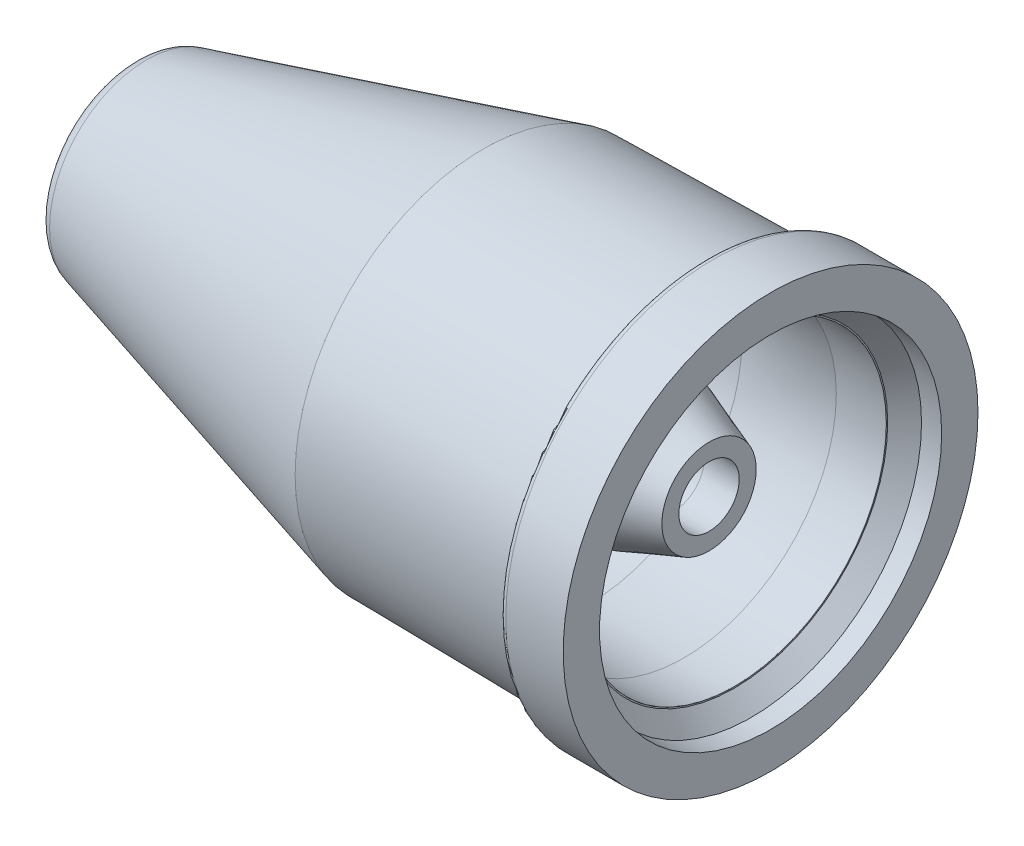
SolidWorks part; units mm, degrees
material "PBT Propósitos gerais"
ref_plane "Frontal" through (0, 0, 0) normal (0, 0, 1) x (1, 0, 0)
ref_plane "Superior" through (0, 0, 0) normal (0, 1, 0) x (1, 0, 0)
ref_plane "Lateral" through (0, 0, 0) normal (1, 0, 0) x (0, 0, -1)
sketch "Sketch1" plane through (0, 0, 0) normal (0, 0, 1) x (1, 0, 0)
  line L0 (3, 0) -> (-11, 0) construction
  line L1 (0, 2.6807) -> (0, 3.25)
  line L2 (0, 3.25) -> (-1, 3.25)
  line L3 (-1, 3.25) -> (-1, 3)
  line L4 (-1, 3) -> (-4.5, 2.951)
  line L5 (-4.5, 2.951) -> (-10, 1.46)
  line L6 (-10, 1.46) -> (-10, 1.1823) construction
  line L7 (-9.57, 0.9) -> (-5.9512, 0.8621) construction
  line L8 (-5.8522, 0.7621) -> (-5.8522, 0.4926)
  line L9 (-5.8522, 0.4926) -> (-1.5277, 0.4926)
  line L10 (-7.53, 1.475) -> (-5.28, 1.475)
  line L11 (-5.28, 1.1084) -> (-1.6842, 1.069)
  line L12 (-5.28, 1.1084) -> (-5.28, 1.25)
  line L13 (-5.28, 1.25) -> (-8.3321, 1.25) construction
  line L14 (-0.3, 2.665) -> (-0.565, 2.4)
  line L15 (-10, 1.1823) -> (-9.8522, 1.1823) construction
  line L16 (-4.81, 2.3268) -> (-0.565, 2.38)
  line L17 (-6.0737, 1.9763) -> (-8.3321, 1.35) construction
  line L18 (-8.3321, 1.35) -> (-8.3321, 1.25) construction
  line L19 (-9.8522, 1.1823) -> (-9.57, 0.9) construction
  line L20 (-4.81, 2.3268) -> (-5.502, 2.1349)
  line L21 (-0.565, 2.38) -> (-0.565, 2.4)
  line L22 (-10, 1.46) -> (-10, 1.182)
  line L23 (-0.3, 2.665) -> (0, 2.6807)
  line L24 (-0.9603, 0.875) -> (-1.6842, 1.069)
  line L25 (-10, 1.182) -> (-9.9422, 1.182)
  line L26 (-9.9422, 1.182) -> (-9.6267, 1.1123)
  line L27 (-9.5482, 1.0147) -> (-9.5482, 0.9111)
  line L28 (-9.5482, 0.9111) -> (-5.9512, 0.8621)
  line L29 (-1.5277, 0.4926) -> (-0.9603, 0.4728)
  line L30 (-0.9603, 0.4728) -> (-0.9603, 0.875)
  line L31 (-5.28, 1.475) -> (-5.28, 1.25)
  line L32 (-7.53, 1.475) -> (-7.53, 1.5724)
  line L33 (-7.53, 1.5724) -> (-6.0737, 1.9763)
  arc A0 (-6.0737, 1.9763) -> (-5.502, 2.1349) centre (-5.8921, 2.4314) ccw
  arc A2 (-9.6267, 1.1123) -> (-9.5482, 1.0147) centre (-9.6482, 1.0147) cw
  arc A3 (-5.8522, 0.7621) -> (-5.9512, 0.8621) centre (-5.9522, 0.7621) ccw
  point P34 (-9.5482, 1.095)
  dimension "D18" = 15.5
  dimension "D27" = 10
  dimension "D31" = 3.8828
  dimension "D7" = 0.601
  dimension "D10" = 0.1
  dimension "D6" = 2.9199
  dimension "D39" = 0.1
  dimension "D37" = 0.49
  dimension "D43" = 0.3
  dimension "D44" = 2.25
  dimension "D46" = 4.8
  dimension "D47" = 5.33
  dimension "D23" = 4.6535
  dimension "D38" = 2.44
  dimension "D48" = 1.8222
  dimension "D52" = 0.1
  dimension "D1" = 6.5
  dimension "D2" = 5.902
  dimension "D3" = 4.5
  dimension "D4" = 1
  dimension "D5" = 3
  dimension "D9" = 4.1478
  dimension "D11" = 0.9852
  dimension "D12" = 1.25
  dimension "D13" = 0.628
  dimension "D14" = 6
  dimension "D15" = 5.28
  dimension "D16" = 4.81
  dimension "D17" = 2.1379
  dimension "D19" = 2.3645
  dimension "D20" = 3.5958
  dimension "D21" = 45
  dimension "D22" = 4.76
  dimension "D24" = 2.7
  dimension "D25" = 2.2167
  dimension "D26" = 3.0521
  dimension "D28" = 0.9603
  dimension "D29" = 45
  dimension "D30" = 8.3321
  dimension "D32" = 1.8
  dimension "D33" = 1.7241
  dimension "D34" = 2.95
  dimension "D35" = 15.168
  dimension "D36" = 5.3614
  dimension "D40" = 0.565
  dimension "D41" = 15
  dimension "D45" = 0.1478
  dimension "D49" = 0.394
  dimension "D50" = 4.09
  dimension "D51" = 2.19
  dimension "D53" = 2.364
  dimension "D54" = 0.9456
  dimension "D56" = 2
revolve "Base-Revolve" add sketch "Sketch1" angle 360 about L0
fillet "Fillet1" radius 0.3 1 edges at (-10, 0, -1.46)
fillet "Fillet2" radius 0.1 1 edges at (-1, 0, -3.25)
scale "Molde (1,5%)" scale about origin uniform scaling yes scale factor 1.015
sketch "Esboço1" plane through (0, 0, 0) normal (0, 0, 1) x (1, 0, 0)
  line L18 (9.9208, -2) -> (9.9208, -0.6)
  line L19 (2.2208, -2) -> (9.9208, -2)
  line L20 (2.2208, -2.1) -> (2.2208, -2)
  line L21 (-0.5792, -2.1) -> (2.2208, -2.1)
  line L22 (-0.5792, -2.425) -> (-0.5792, -2.1)
  line L23 (-1.3798, -2.425) -> (-0.5792, -2.425)
  line L24 (-4.8892, -2.425) -> (-2.8798, -2.425)
  line L25 (-4.9853, -2.3974) -> (-4.8892, -2.425)
  line L26 (-5.7792, -2.1698) -> (-5.6582, -2.2045)
  line L27 (-5.7792, -1.5) -> (-5.7792, -2.1698)
  line L28 (-5.3592, -1.5) -> (-5.7792, -1.5)
  line L29 (-5.3592, -1.125) -> (-5.3592, -1.5)
  line L30 (-1.8996, -1.085) -> (-5.3592, -1.125)
  line L31 (-0.9792, -0.75) -> (-1.8996, -1.085)
  line L32 (-0.9792, -0.48) -> (-0.9792, -0.75)
  line L33 (1.3117, -0.4) -> (-0.9792, -0.48)
  line L34 (1.4272, -0.6) -> (1.3117, -0.4)
  line L35 (9.9208, -0.6) -> (1.4272, -0.6)
  line L40 (-0.5792, -2.425) -> (-0.5735, -0.48)
  line L41 (-1.3798, -2.425) -> (-0.5792, -2.425)
  line L42 (-4.8892, -2.425) -> (-2.8798, -2.425)
  line L43 (-4.9853, -2.3974) -> (-4.8892, -2.425)
  line L44 (-5.7792, -2.1698) -> (-5.6582, -2.2045)
  line L45 (-5.7792, -1.5) -> (-5.7792, -2.1698)
  line L46 (-5.3592, -1.5) -> (-5.7792, -1.5)
  line L47 (-5.3592, -1.125) -> (-5.3592, -1.5)
  line L48 (-1.8996, -1.085) -> (-5.3592, -1.125)
  line L49 (-0.9792, -0.75) -> (-1.8996, -1.085)
  line L50 (-0.9792, -0.48) -> (-0.9792, -0.75)
  line L54 (0, 0) -> (-10.1813, 0) construction
  line L55 (0, -3.2988) -> (0, 3.2988) construction
  line L56 (-0.9792, -0.48) -> (-0.5735, -0.48)
  line L57 (-0.5735, -2.436) -> (-0.5735, 2.436) construction
  arc A2 (-1.3798, -2.425) -> (-2.8798, -2.425) centre (-2.1298, -8.025) ccw
  arc A3 (-4.9853, -2.3974) -> (-5.6582, -2.2045) centre (-5.4202, -2.6442) ccw
  arc A4 (-1.3798, -2.425) -> (-2.8798, -2.425) centre (-2.1298, -8.025) ccw
  arc A5 (-4.9853, -2.3974) -> (-5.6582, -2.2045) centre (-5.4202, -2.6442) ccw
  dimension "D1" = 0
revolve "Corte-Revolução1" cut sketch "Esboço1" angle 360 about L54
sketch "Esboço2" plane through (0, 0, 0) normal (0, 0, 1) x (1, 0, 0)
  line L0 (-10.7206, 0) -> (0.5542, 0) construction
  line L1 (-2.8798, -2.425) -> (-2.8798, -2.5441)
  line L2 (-2.8798, -2.5441) -> (-1.3798, -2.5441)
  line L3 (-1.3798, -2.5441) -> (-1.3798, -2.425)
  line L6 (-5.7792, -2.1698) -> (-5.6582, -2.2045) construction
  line L7 (-5.7792, -2.1698) -> (-5.6582, -2.2045)
  line L8 (-5.7792, -1.5) -> (-5.7792, -2.1698) construction
  line L9 (-5.7792, -1.3306) -> (-5.7792, -2.1698)
  line L10 (-5.7792, -1.3306) -> (-7.8738, -1.3516)
  line L11 (-7.8738, -1.3516) -> (-7.8738, -1.6965)
  line L12 (-7.8738, -1.6965) -> (-4.9303, -2.544)
  arc A0 (-4.9853, -2.3974) -> (-5.6582, -2.2045) centre (-5.4202, -2.6442) ccw construction
  arc A1 (-4.9303, -2.544) -> (-5.6582, -2.2045) centre (-5.4202, -2.6442) ccw
  arc A2 (-1.3798, -2.425) -> (-2.8798, -2.425) centre (-2.1298, -8.025) ccw construction
  arc A3 (-1.3798, -2.425) -> (-2.8798, -2.425) centre (-2.1298, -8.025) ccw
  dimension "D1" = 0.1191
revolve "Revolução1" add sketch "Esboço2" angle 360 about L0
scale "Escala1" scale about centroid uniform scaling yes scale factor 0.985
